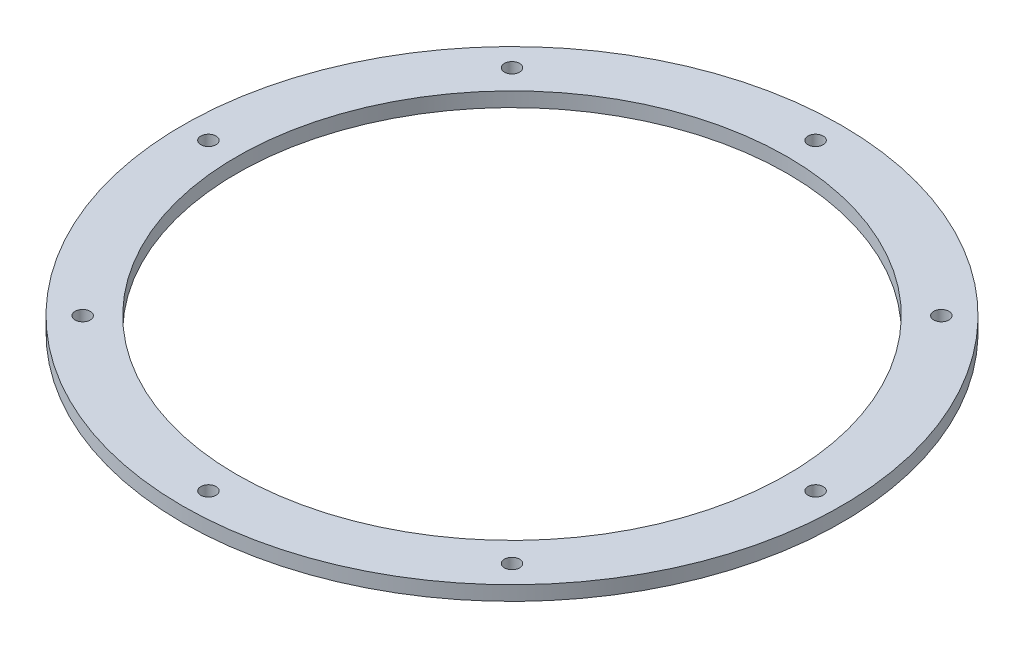
SolidWorks part; units mm, degrees
material "Thornel Mat VMA"
ref_plane "前视基准面" through (0, 0, 0) normal (0, 0, 1) x (1, 0, 0)
ref_plane "上视基准面" through (0, 0, 0) normal (0, 1, 0) x (1, 0, 0)
ref_plane "右视基准面" through (0, 0, 0) normal (1, 0, 0) x (0, 0, -1)
other "Configuration Table"
sketch "草图1" plane through (0, 0, 0) normal (0, 0, 1) x (1, 0, 0)
  line L0 (0, 0) -> (0, 28.7896) construction
  line L2 (76.08, 15.905) -> (91.08, 15.905)
  line L3 (76.08, 15.905) -> (76.08, 19.905)
  line L4 (76.08, 19.905) -> (91.08, 19.905)
  line L5 (91.08, 15.905) -> (91.08, 19.905)
  dimension "D1" = 91.08
  dimension "D2" = 15
  dimension "D3" = 4
revolve "旋转1" add sketch "草图1" angle 360 about L0
sketch "草图2" plane through (0, 19.905, 0) normal (0, 1, 0) x (1, 0, 0)
  circle A0 centre (0, 0) radius 83.9 construction
  circle A1 centre (-83.9, 0) radius 2.1
  circle A2 centre (-59.3263, 59.3263) radius 2.1
  circle A3 centre (0, 83.9) radius 2.1
  circle A4 centre (59.3263, 59.3263) radius 2.1
  circle A5 centre (83.9, 0) radius 2.1
  circle A6 centre (59.3263, -59.3263) radius 2.1
  circle A7 centre (0, -83.9) radius 2.1
  circle A8 centre (-59.3263, -59.3263) radius 2.1
  point P22 (0, 0)
  dimension "D1" = 167.8
  dimension "D2" = 4.2
  dimension "D3" = 8
extrude "切除-拉伸1" cut sketch "草图2" against normal blind 10
